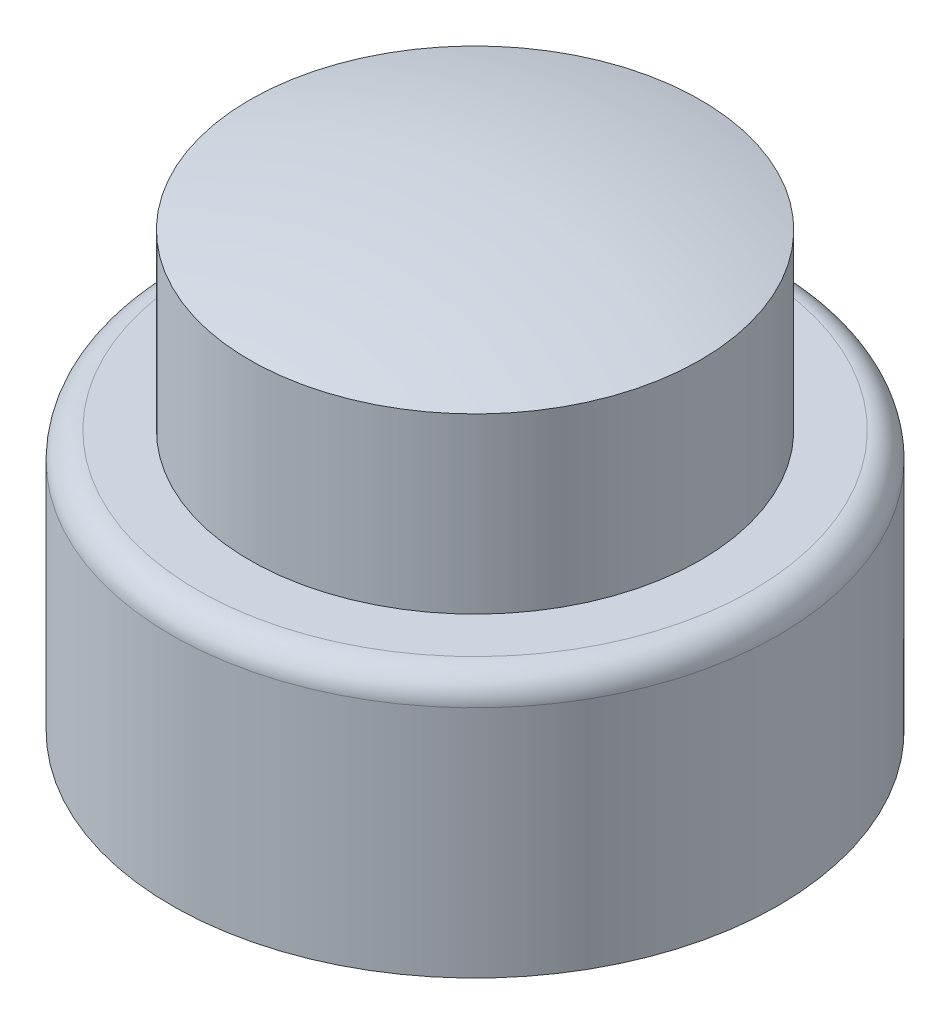
SolidWorks part; units mm, degrees
ref_plane "Front Plane" through (0, 0, 0) normal (0, 0, 1) x (1, 0, 0)
ref_plane "Top Plane" through (0, 0, 0) normal (0, 1, 0) x (1, 0, 0)
ref_plane "Right Plane" through (0, 0, 0) normal (1, 0, 0) x (0, 0, -1)
sketch "Sketch1" plane through (0, 0, 0) normal (0, 0, 1) x (1, 0, 0)
  line L1 (-1.3, 2.5) -> (-1.3, 1.5)
  line L2 (-1.3, 1.5) -> (-1.75, 1.5)
  line L3 (-1.75, 1.5) -> (-1.75, 0)
  line L4 (-1.75, 0) -> (0, 0)
  line L5 (0, 0) -> (0, 2.672)
  arc A0 (0, 2.672) -> (-1.3, 2.5) centre (0, -2.328) ccw
  point P7 (0, 0)
  point P9 (0, 2.0325)
  point P10 (0, 0)
  point P11 (0, 0)
  dimension "D2" = 10
  dimension "D1" = 1
  dimension "D3" = 1.3
  dimension "D4" = 1.75
  dimension "D5" = 1.5
revolve "Revolve1" add sketch "Sketch1" angle 360 about L5
fillet "Fillet1" radius 0.15 1 edges at (1.75, 1.5, 0)
